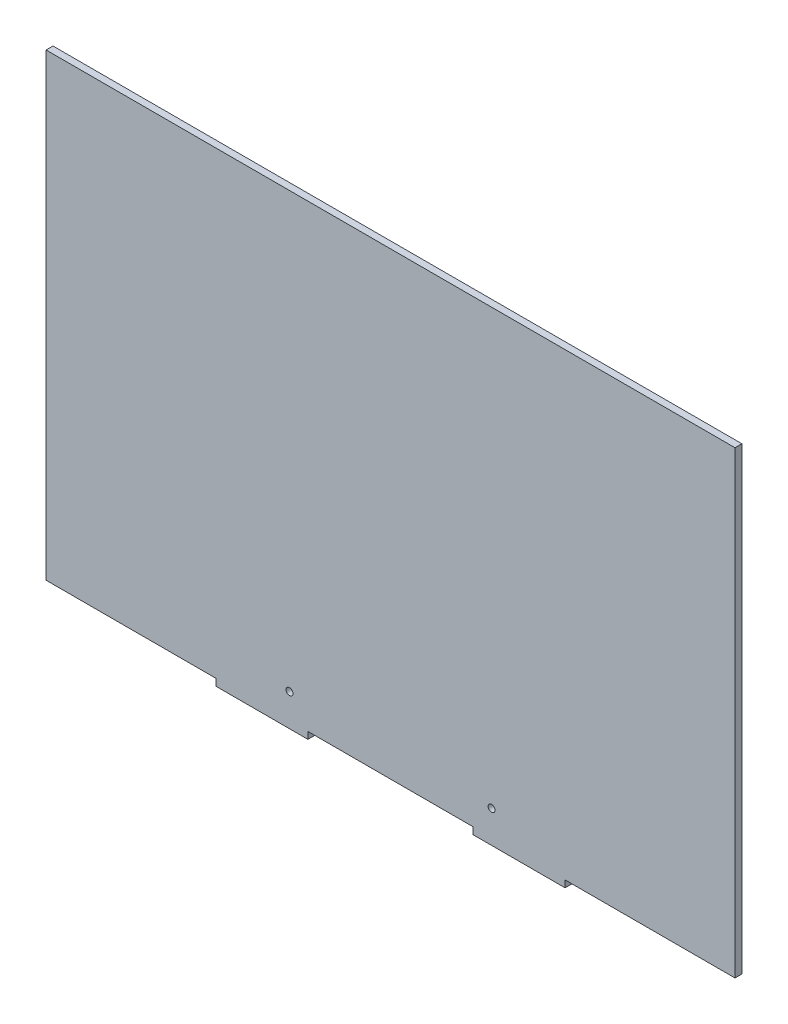
SolidWorks part; units mm, degrees
ref_plane "Plano frontal" through (0, 0, 0) normal (0, 0, 1) x (1, 0, 0)
ref_plane "Plano superior" through (0, 0, 0) normal (0, 1, 0) x (1, 0, 0)
ref_plane "Plano direito" through (0, 0, 0) normal (1, 0, 0) x (0, 0, -1)
sketch "Esboço1" plane through (0, 0, 0) normal (0, 0, 1) x (1, 0, 0)
  line L0 (-58.0463, -5.6704) -> (13.9537, -5.6704)
  line L1 (-172.0463, 194.3296) -> (127.9537, 194.3296)
  line L2 (-172.0463, 194.3296) -> (-172.0463, -5.6704)
  line L3 (-172.0463, -5.6704) -> (-98.0463, -5.6704)
  line L4 (127.9537, 194.3296) -> (127.9537, -5.6704)
  line L5 (53.9537, -5.6704) -> (127.9537, -5.6704)
  line L6 (-98.0463, -5.6704) -> (-98.0463, -8.6704)
  line L7 (-98.0463, -8.6704) -> (-58.0463, -8.6704)
  line L8 (-58.0463, -5.6704) -> (-58.0463, -8.6704)
  line L10 (53.9537, -5.6704) -> (53.9537, -8.6704)
  line L11 (53.9537, -8.6704) -> (13.9537, -8.6704)
  line L12 (13.9537, -5.6704) -> (13.9537, -8.6704)
  point P12 (13.9537, -7.1704)
  dimension "D1" = 3
  dimension "D2" = 3
  dimension "D3" = 300
  dimension "D4" = 40
  dimension "D5" = 72
  dimension "D6" = 40
  dimension "D7" = 74
  dimension "D8" = 200
extrude "Ressalto-extrusão1" add sketch "Esboço1" along normal blind 3 contours L4 L1 L2 L3
sketch "Esboço2" plane through (0, 0, 3) normal (0, 0, 1) x (1, 0, 0)
  line L0 (127.9537, 194.3296) -> (127.9537, -5.6704) construction
  line L1 (-172.0463, 194.3296) -> (-172.0463, -5.6704) construction
  line L2 (-172.0463, -5.6704) -> (-98.0463, -5.6704) construction
  line L3 (-58.0463, -5.6704) -> (13.9537, -5.6704) construction
  circle A0 centre (-66.0463, 5.3296) radius 1.5
  circle A1 centre (21.9537, 5.3296) radius 1.5
  dimension "D1" = 106
  dimension "D2" = 3
  dimension "D3" = 106
  dimension "D4" = 3
  dimension "D5" = 11
  dimension "D6" = 11
extrude "Corte-extrusão1" cut sketch "Esboço2" against normal through all
